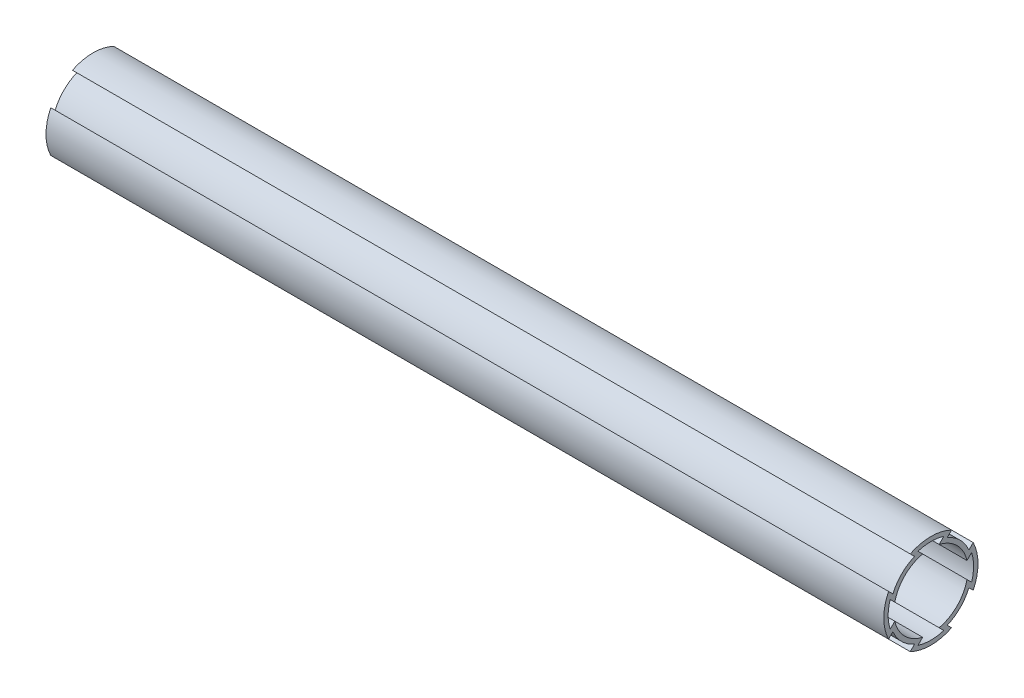
SolidWorks part; units mm, degrees
material "6063-T5"
ref_plane "Front Plane" through (0, 0, 0) normal (0, 0, 1) x (1, 0, 0)
ref_plane "Top Plane" through (0, 0, 0) normal (0, 1, 0) x (1, 0, 0)
ref_plane "Right Plane" through (0, 0, 0) normal (1, 0, 0) x (0, 0, -1)
other "Center of Mass"
sketch "Sketch1" plane through (0, 0, 0) normal (1, 0, 0) x (0, 0, -1)
  line L16 (-11.2978, 4.8631) -> (-12.5794, 6.1448)
  line L17 (-12.5794, -6.1448) -> (-11.2978, -4.8631)
  line L18 (-4.8631, -11.2978) -> (-6.1448, -12.5794)
  line L19 (6.1448, -12.5794) -> (4.8631, -11.2978)
  line L20 (11.2978, -4.8631) -> (12.5794, -6.1448)
  line L21 (12.5794, 6.1448) -> (11.2978, 4.8631)
  line L22 (4.8631, 11.2978) -> (6.1448, 12.5794)
  line L23 (-6.1448, 12.5794) -> (-4.8631, 11.2978)
  line L24 (-10.7236, 2.4504) -> (-12.1074, 3.8342)
  line L25 (-12.1074, -3.8342) -> (-10.7236, -2.4504)
  line L26 (-2.4504, -10.7236) -> (-3.8342, -12.1074)
  line L27 (3.8342, -12.1074) -> (2.4504, -10.7236)
  line L28 (10.7236, -2.4504) -> (12.1074, -3.8342)
  line L29 (12.1074, 3.8342) -> (10.7236, 2.4504)
  line L30 (2.4504, 10.7236) -> (3.8342, 12.1074)
  line L31 (-3.8342, 12.1074) -> (-2.4504, 10.7236)
  arc A18 (-12.5794, 6.1448) -> (-12.5794, -6.1448) centre (0, 0) ccw
  arc A19 (-11.2978, -4.8631) -> (-4.8631, -11.2978) centre (0, 0) ccw
  arc A20 (-6.1448, -12.5794) -> (6.1448, -12.5794) centre (0, 0) ccw
  arc A21 (4.8631, -11.2978) -> (11.2978, -4.8631) centre (0, 0) ccw
  arc A22 (12.5794, -6.1448) -> (14, 0) centre (0, 0) ccw
  arc A23 (14, 0) -> (12.5794, 6.1448) centre (0, 0) ccw
  arc A24 (11.2978, 4.8631) -> (4.8631, 11.2978) centre (0, 0) ccw
  arc A25 (6.1448, 12.5794) -> (-6.1448, 12.5794) centre (0, 0) ccw
  arc A26 (-4.8631, 11.2978) -> (-11.2978, 4.8631) centre (0, 0) ccw
  arc A27 (-12.1074, 3.8342) -> (-12.1074, -3.8342) centre (0, 0) ccw
  arc A28 (-10.7236, -2.4504) -> (-2.4504, -10.7236) centre (0, 0) ccw
  arc A29 (-3.8342, -12.1074) -> (3.8342, -12.1074) centre (0, 0) ccw
  arc A30 (2.4504, -10.7236) -> (10.7236, -2.4504) centre (0, 0) ccw
  arc A31 (12.1074, -3.8342) -> (12.7, 0) centre (0, 0) ccw
  arc A32 (12.7, 0) -> (12.1074, 3.8342) centre (0, 0) ccw
  arc A33 (10.7236, 2.4504) -> (2.4504, 10.7236) centre (0, 0) ccw
  arc A34 (3.8342, 12.1074) -> (-3.8342, 12.1074) centre (0, 0) ccw
  arc A35 (-2.4504, 10.7236) -> (-10.7236, 2.4504) centre (0, 0) ccw
  dimension "D1" = 1.3
extrude "Boss-Extrude1" add sketch "Sketch1" along normal blind 249
